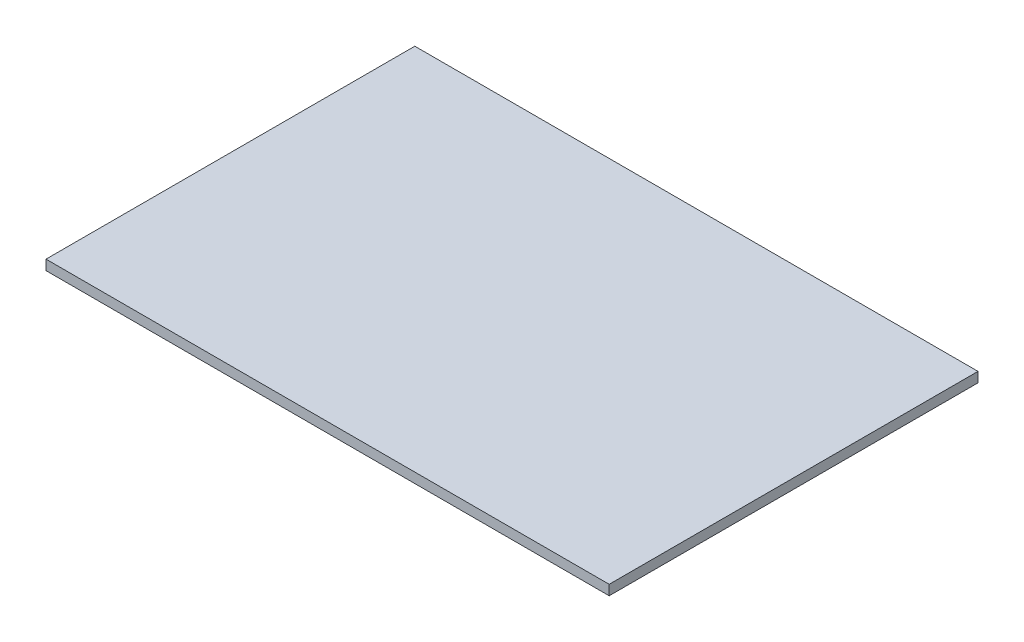
SolidWorks part; units mm, degrees
ref_plane "Front Plane" through (0, 0, 0) normal (0, 0, 1) x (1, 0, 0)
ref_plane "Top Plane" through (0, 0, 0) normal (0, 1, 0) x (1, 0, 0)
ref_plane "Right Plane" through (0, 0, 0) normal (1, 0, 0) x (0, 0, -1)
sketch "Sketch2" plane through (0, 0, 0) normal (0, 1, 0) x (1, 0, 0)
  line L1 (-282.5, -185) -> (282.5, -185)
  line L2 (-282.5, -185) -> (-282.5, 185)
  line L3 (-282.5, 185) -> (282.5, 185)
  line L4 (282.5, -185) -> (282.5, 185)
  line L5 (-282.5, -185) -> (282.5, 185) construction
  line L6 (-282.5, 185) -> (282.5, -185) construction
  point P0 (0, 0)
  dimension "D1" = 565
  dimension "D2" = 370
extrude "Boss-Extrude1" add sketch "Sketch2" along normal blind 10
